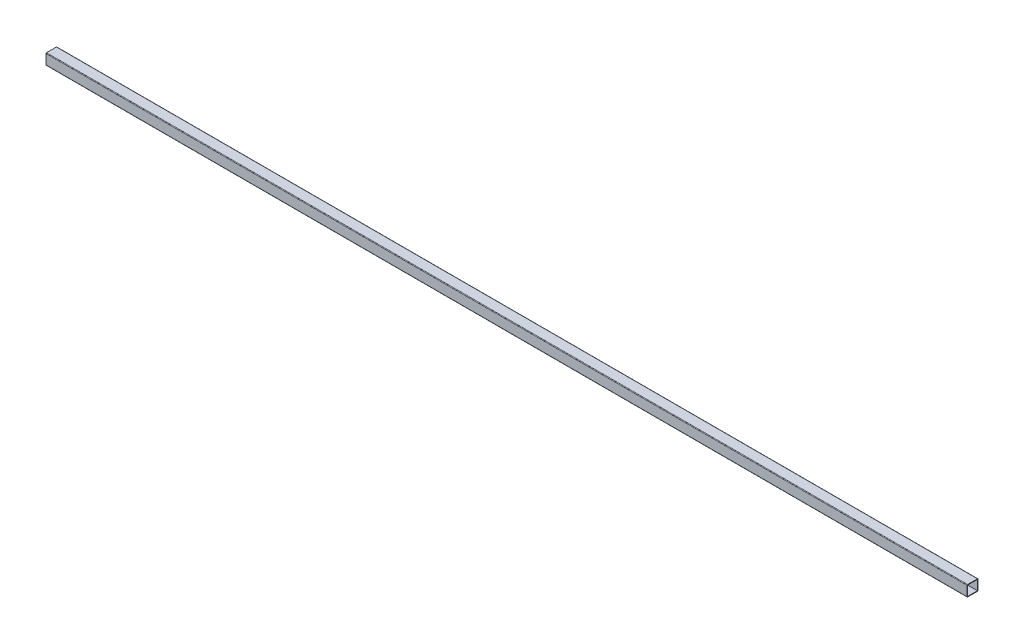
SolidWorks part; units mm, degrees
material "Простая углеродистая сталь"
ref_plane "Спереди" through (0, 0, 0) normal (0, 0, 1) x (1, 0, 0)
ref_plane "Сверху" through (0, 0, 0) normal (0, 1, 0) x (1, 0, 0)
ref_plane "Справа" through (0, 0, 0) normal (1, 0, 0) x (0, 0, -1)
sketch "Эскиз1" plane through (0, 0, 0) normal (0, 0, 1) x (1, 0, 0)
  line L0 (0, 0) -> (5080, 0)
  dimension "D1" = 5080
other "Квадратная труба гост 8639-82 _60 X 60 X 3.0(1)"
ref_plane "Плоскость1" through (0, 0, 0) normal (1, 0, 0) x (0, 1, 0)
sketch "Sketch1" plane through (0, 0, 0) normal (1, 0, 0) x (0, 1, 0)
  line L0 (-26.999, -27) -> (26.999, -27)
  line L1 (-27, -26.999) -> (-27, 26.999)
  line L2 (26.999, 27) -> (-26.999, 27)
  line L3 (27, 26.999) -> (27, -26.999)
  line L4 (-26.999, -30) -> (26.999, -30)
  line L5 (-30, -26.999) -> (-30, 26.999)
  line L6 (26.999, 30) -> (-26.999, 30)
  line L7 (30, 26.999) -> (30, -26.999)
  arc A0 (30, 26.999) -> (26.999, 30) centre (26.999, 26.999) ccw
  arc A1 (26.999, -30) -> (30, -26.999) centre (26.999, -26.999) ccw
  arc A2 (-30, -26.999) -> (-26.999, -30) centre (-26.999, -26.999) ccw
  arc A3 (-26.999, 30) -> (-30, 26.999) centre (-26.999, 26.999) ccw
  arc A4 (-26.999, 27) -> (-27, 26.999) centre (-26.999, 26.999) ccw
  arc A5 (27, 26.999) -> (26.999, 27) centre (26.999, 26.999) ccw
  arc A6 (26.999, -27) -> (27, -26.999) centre (26.999, -26.999) ccw
  arc A7 (-27, -26.999) -> (-26.999, -27) centre (-26.999, -26.999) ccw
  point P0 (-30, 0)
  point P1 (30, 0)
  point P2 (0, 30)
  point P3 (0, -30)
  point P4 (0, 0)
  point P5 (-30, -30)
  point P6 (30, -30)
  point P7 (30, 30)
  point P8 (-30, 30)
  point P33 (0, 0)
  dimension "D1" = 3.001
  dimension "Thickness" = 3
  dimension "V_leg" = 60
equation "\"D1@Sketch1\" = \"Thickness@Sketch1\"+0.001"
